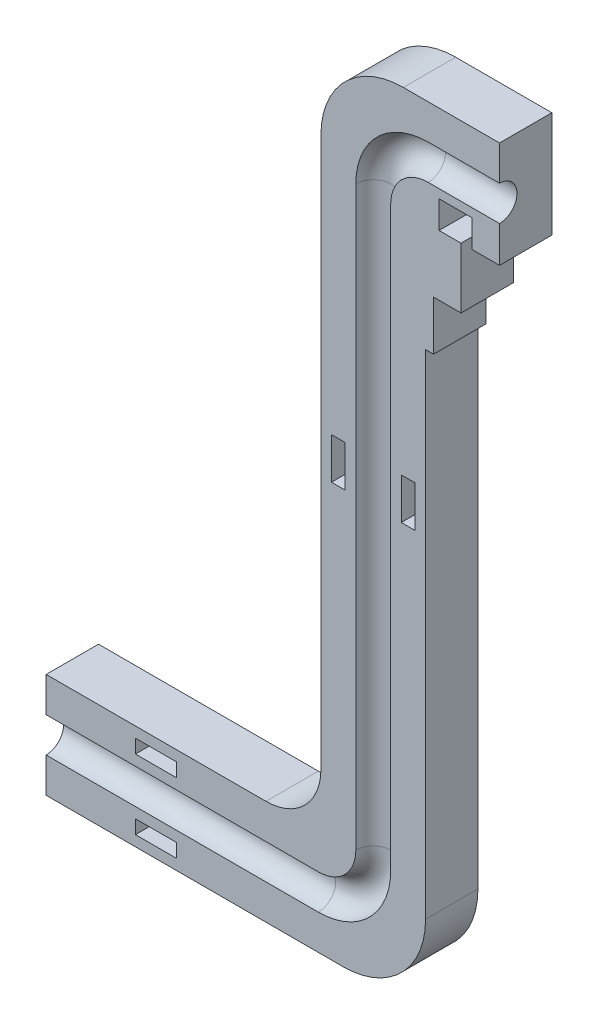
SolidWorks part; units mm, degrees
material "ABS"
ref_plane "Front Plane" through (0, 0, 0) normal (0, 0, 1) x (1, 0, 0)
ref_plane "Top Plane" through (0, 0, 0) normal (0, 1, 0) x (1, 0, 0)
ref_plane "Right Plane" through (0, 0, 0) normal (1, 0, 0) x (0, 0, -1)
sketch "Sketch1" plane through (0, 0, 0) normal (0, 0, 1) x (1, 0, 0)
  line L0 (-100, 0) -> (0, 0)
  line L1 (0, 0) -> (0, 250)
  line L2 (0, 250) -> (65, 250)
  line L3 (65, 250) -> (65, 211.9)
  line L4 (-100, -38.1) -> (38.1, -38.1)
  line L5 (38.1, -38.1) -> (38.1, 211.9)
  line L6 (38.1, 211.9) -> (65, 211.9)
  line L7 (-100, 0) -> (-100, -38.1)
  dimension "D1" = 100
  dimension "D2" = 250
  dimension "D3" = 65
  dimension "D4" = 38.1
extrude "Boss-Extrude1" add sketch "Sketch1" along normal blind 19.05
sketch "Sketch2" plane through (0, 0, 0) normal (0, 0, -1) x (-1, 0, 0)
  line L0 (-65, 230.95) -> (-39.05, 230.95)
  line L1 (-65, 211.9) -> (-65, 250) construction
  line L2 (100, -19.05) -> (0.95, -19.05)
  line L3 (100, 0) -> (100, -38.1) construction
  line L5 (-19.05, 210.95) -> (-19.05, 0.95)
  line L7 (-38.1, -38.1) -> (-38.1, 211.9) construction
  arc A0 (0.95, -19.05) -> (-19.05, 0.95) centre (0.95, 0.95) cw
  arc A1 (-39.05, 230.95) -> (-19.05, 210.95) centre (-39.05, 210.95) cw
  dimension "D2" = 20
  dimension "D1" = 19.05
fillet "Fillet1" radius 30 2 edges at (38.1, -38.1, 9.525) (0, 250, 9.525)
fillet "Fillet2" radius 20 1 edges at (0, 0, 9.525)
sketch "Sketch13" plane through (0, 0, 19.05) normal (0, 0, 1) x (1, 0, 0)
  line L0 (38.1, 221.425) -> (38.1, 140.9734) construction
  line L1 (38.1, -8.1) -> (38.1, 211.9) construction
  line L2 (65, 230.95) -> (65, 211.9) construction
  line L3 (65, 221.425) -> (38.1, 221.425) construction
  line L4 (55, 221.425) -> (43, 221.425)
  line L5 (43, 221.425) -> (43, 211.425)
  line L6 (55, 221.425) -> (55, 211.425)
  line L7 (43, 211.425) -> (51, 211.425)
  line L8 (51, 211.425) -> (51, 189.425)
  line L9 (55, 211.425) -> (65, 211.425)
  line L11 (51, 189.425) -> (41, 189.425)
  line L12 (41, 189.425) -> (41, 171.425)
  line L13 (41, 171.425) -> (36.5499, 171.425)
  line L14 (36.5499, 171.425) -> (36.5499, 223.573)
  line L15 (36.5499, 223.573) -> (65, 223.573)
  line L16 (65, 223.573) -> (65, 211.9)
  line L18 (65, 211.9) -> (65, 211.425)
  dimension "D1" = 10
  dimension "D2" = 12
  dimension "D3" = 10
  dimension "D4" = 10
  dimension "D5" = 8
  dimension "D6" = 22
  dimension "D7" = 10
  dimension "D8" = 18
  dimension "D9" = 52.148
extrude "Boss-Extrude3" add sketch "Sketch13" against normal blind 19.05
sketch "Sketch14" plane through (0, 0, 19.05) normal (0, 0, 1) x (1, 0, 0)
  line L0 (65, 211.425) -> (65, 250) construction
  line L1 (55, 221.42) -> (43, 221.42)
  line L2 (55, 221.42) -> (55, 211.42)
  line L3 (55, 211.42) -> (43, 211.42)
  line L4 (43, 221.42) -> (43, 211.42)
  line L5 (55, 221.42) -> (43, 211.42) construction
  line L6 (55, 211.42) -> (43, 221.42) construction
  line L7 (65, 230.95) -> (39.05, 230.95) construction
  point P0 (49, 216.42)
  dimension "D1" = 10
  dimension "D2" = 12
  dimension "D3" = 10
  dimension "D4" = 9.53
extrude "Cut-Extrude1" cut sketch "Sketch14" against normal blind 39
sketch "Sketch17" plane through (0, 0, 19.05) normal (0, 0, 1) x (1, 0, 0)
  line L0 (65, 230.95) -> (39.05, 230.95)
  line L1 (19.05, 210.95) -> (19.05, 0.95)
  line L2 (-0.95, -19.05) -> (-100, -19.05)
  arc A1 (39.05, 230.95) -> (19.05, 210.95) centre (39.05, 210.95) ccw
  arc A2 (19.05, 0.95) -> (-0.95, -19.05) centre (-0.95, 0.95) cw
sweep "Cut-Sweep1" cut path "Sketch17" circular profile diameter 12.7 parameters "D3"=12.7
sketch "Sketch24" plane through (0, 0, 19.05) normal (0, 0, 1) x (1, 0, 0)
  line L0 (0, 120) -> (12.7, 120) construction
  line L1 (0, 220) -> (0, 20) construction
  line L2 (12.7, 0.95) -> (12.7, 210.95) construction
  line L3 (19.05, 210.95) -> (19.05, 0.95) construction
  line L4 (-100, -19.05) -> (-0.95, -19.05) construction
  line L5 (-60, 0) -> (-60, -12.7) construction
  line L6 (-20, 0) -> (-100, 0) construction
  line L7 (-100, -12.7) -> (-0.95, -12.7) construction
  line L8 (29.25, 112.5) -> (34.25, 127.5) construction
  line L9 (8.85, 127.5) -> (3.85, 127.5)
  line L10 (8.85, 127.5) -> (8.85, 112.5)
  line L11 (8.85, 112.5) -> (3.85, 112.5)
  line L12 (3.85, 127.5) -> (3.85, 112.5)
  line L13 (8.85, 127.5) -> (3.85, 112.5) construction
  line L14 (8.85, 112.5) -> (3.85, 127.5) construction
  line L15 (-52.5, -3.85) -> (-67.5, -3.85)
  line L16 (-52.5, -3.85) -> (-52.5, -8.85)
  line L17 (-52.5, -8.85) -> (-67.5, -8.85)
  line L18 (-67.5, -3.85) -> (-67.5, -8.85)
  line L19 (-52.5, -3.85) -> (-67.5, -8.85) construction
  line L20 (-52.5, -8.85) -> (-67.5, -3.85) construction
  line L21 (29.25, 127.5) -> (34.25, 112.5) construction
  line L22 (38.1, 120) -> (25.4, 120) construction
  line L23 (34.25, 127.5) -> (34.25, 112.5)
  line L24 (29.25, 112.5) -> (34.25, 112.5)
  line L25 (29.25, 127.5) -> (29.25, 112.5)
  line L26 (29.25, 127.5) -> (34.25, 127.5)
  line L27 (-52.5, -29.25) -> (-67.5, -34.25) construction
  line L28 (-52.5, -34.25) -> (-67.5, -29.25) construction
  line L29 (-60, -38.1) -> (-60, -25.4) construction
  line L30 (-67.5, -34.25) -> (-67.5, -29.25)
  line L31 (-52.5, -29.25) -> (-67.5, -29.25)
  line L32 (-52.5, -34.25) -> (-52.5, -29.25)
  line L33 (-52.5, -34.25) -> (-67.5, -34.25)
  point P20 (6.35, 120)
  point P25 (-60, -6.35)
  point P36 (31.75, 120)
  point P43 (-60, -31.75)
  dimension "D1" = 5
  dimension "D2" = 15
  dimension "D3" = 5
  dimension "D4" = 15
extrude "Cut-Extrude2" cut sketch "Sketch24" against normal blind 10
